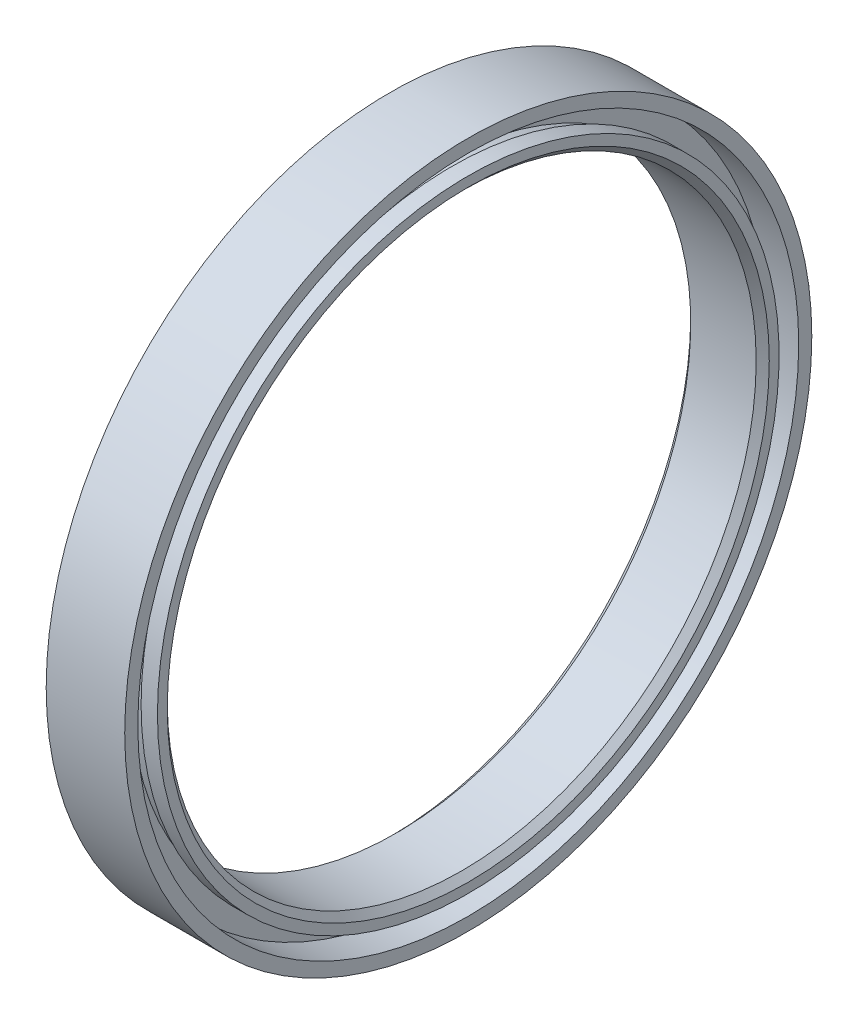
SolidWorks part; units mm, degrees
ref_plane "前视基准面" through (0, 0, 0) normal (0, 0, 1) x (1, 0, 0)
ref_plane "上视基准面" through (0, 0, 0) normal (0, 1, 0) x (1, 0, 0)
ref_plane "右视基准面" through (0, 0, 0) normal (1, 0, 0) x (0, 0, -1)
other "Configuration Table"
ref_plane "基准面1" through (0, 0, 0) normal (0, 0, -1) x (-1, 0, 0)
sketch "草图1" plane through (0, 0, 0) normal (0, 0, -1) x (-1, 0, 0)
  line L0 (-7, 46.5) -> (-9.5, 46.5)
  line L1 (-9.5, 46.5) -> (-9.5, 47.5)
  line L2 (-9.5, 47.5) -> (-12, 47.5)
  line L3 (-12, 47.5) -> (-12, 45)
  line L4 (-12, 45) -> (0, 45)
  line L7 (0, 45) -> (0, 52.5)
  line L8 (0, 52.5) -> (-12, 52.5)
  line L9 (-12, 52.5) -> (-12, 50.5)
  line L10 (-12, 50.5) -> (-7, 50.5)
  line L11 (-7, 50.5) -> (-7, 46.5)
  line L12 (-17.9104, 0) -> (0, 0) construction
  line L13 (0, 0) -> (85.2609, 0) construction
  dimension "D1" = 2.5
  dimension "D2" = 45
  dimension "D3" = 12
  dimension "D4" = 105
  dimension "D5" = 2.5
  dimension "D6" = 1
  dimension "D9" = 5
  dimension "D10" = 4
  dimension "D11" = 2.5
revolve "旋转1" add sketch "草图1" angle 360 about L12
sketch "草图2" plane through (0, 0, 0) normal (-1, 0, 0) x (0, 0, 1)
  line L0 (-47.4349, -2.486) -> (-50.4308, -2.643)
  line L1 (-50.4308, 2.643) -> (-47.4349, 2.486)
  arc A0 (-50.4308, -2.643) -> (-50.4308, 2.643) centre (0, 0) cw
  arc A1 (-47.4349, 2.486) -> (-47.4349, -2.486) centre (0, 0) ccw
  circle A2 centre (0, 0) radius 47.5 construction
  circle A3 centre (0, 0) radius 50.5 construction
  point P9 (-47.5, 0)
  dimension "D1" = 6
extrude "切除-拉伸1" cut sketch "草图2" against normal blind 0.5
pattern_circular "阵列(圆周)1" count 12 over 360 about axis through (0, 0, 0) along (1, 0, 0) of "切除-拉伸1"
chamfer "倒角1" distance 1 angle 45 2 edges at (12, 0, 45) (0, 0, 45)
